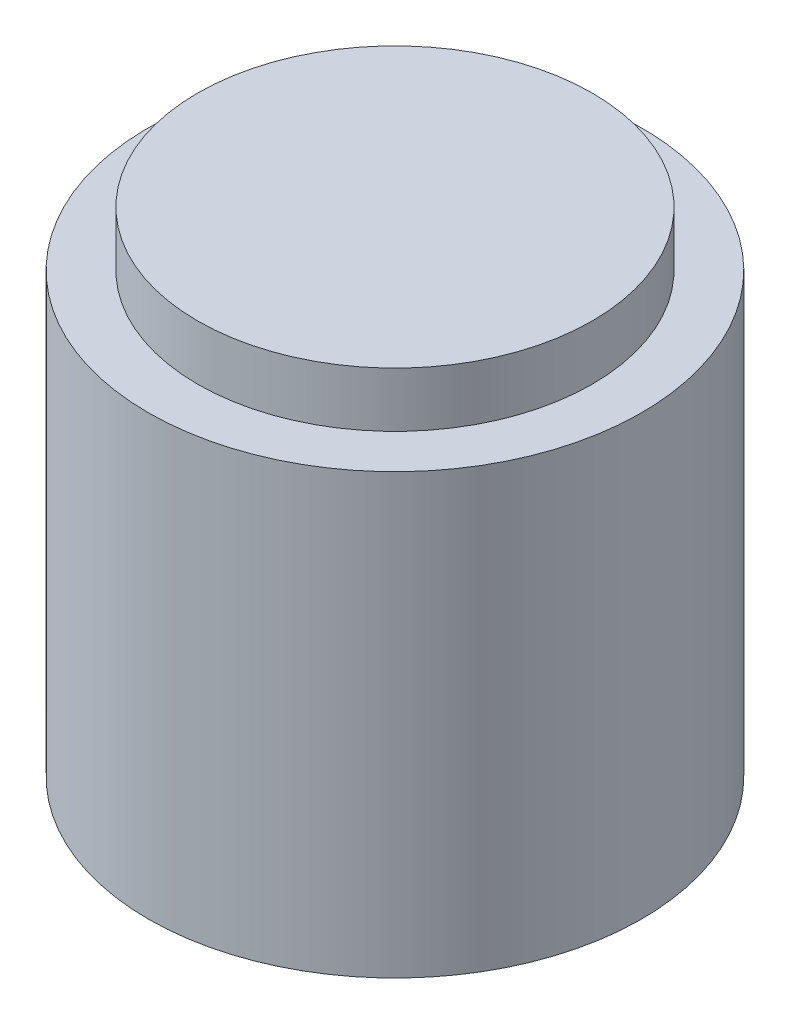
SolidWorks part; units mm, degrees
ref_plane "Front Plane" through (0, 0, 0) normal (0, 0, 1) x (1, 0, 0)
ref_plane "Top Plane" through (0, 0, 0) normal (0, 1, 0) x (1, 0, 0)
ref_plane "Right Plane" through (0, 0, 0) normal (1, 0, 0) x (0, 0, -1)
sketch "Sketch1" plane through (0, 0, 0) normal (0, 1, 0) x (1, 0, 0)
  circle A0 centre (0, 0) radius 7.1438
  dimension "D1" = 14.2875
extrude "Boss-Extrude1" add sketch "Sketch1" along normal blind 12.7
sketch "Sketch2" [suppressed] plane through (0, 12.7, 0) normal (0, 1, 0) x (1, 0, 0)
  line L0 (0, -7.1438) -> (0, -6.35) construction
  line L1 (-7.1438, 0) -> (-6.35, 0) construction
  line L2 (1.27, 6.2217) -> (1.27, 7.03)
  line L4 (-1.27, -7.03) -> (-1.27, -6.2217)
  line L5 (1.0204, 6.2675) -> (1.1479, 7.0509) construction
  line L6 (1.27, -7.03) -> (1.27, -6.2217)
  line L7 (-1.1479, -7.0509) -> (-1.0204, -6.2675) construction
  line L8 (-1.1479, 7.0509) -> (-1.0204, 6.2675) construction
  line L9 (-7.03, 1.27) -> (-6.2217, 1.27)
  line L11 (-7.03, -1.27) -> (-6.2217, -1.27)
  line L13 (-7.0715, 1.0137) -> (-6.2857, 0.9011) construction
  line L14 (-7.0715, -1.0137) -> (-6.2857, -0.9011) construction
  line L15 (0, 6.35) -> (0, 7.1438) construction
  line L17 (-1.27, 6.2217) -> (-1.27, 7.03)
  line L21 (6.2217, -1.27) -> (7.03, -1.27)
  line L22 (6.2217, 1.27) -> (7.03, 1.27)
  line L23 (6.2857, 0.9011) -> (7.0715, 1.0137) construction
  line L24 (6.35, 0) -> (7.1438, 0) construction
  line L25 (6.2857, -0.9011) -> (7.0715, -1.0137) construction
  line L26 (1.0204, -6.2675) -> (1.1479, -7.0509) construction
  arc A0 (1.27, 7.03) -> (-1.27, 7.03) centre (0, 0) ccw
  arc A1 (1.27, 6.2217) -> (-1.27, 6.2217) centre (0, 0) ccw
  arc A2 (-6.2217, 1.27) -> (-6.2217, -1.27) centre (0, 0) ccw
  arc A3 (-7.03, 1.27) -> (-7.03, -1.27) centre (0, 0) ccw
  arc A4 (7.03, -1.27) -> (7.03, 1.27) centre (0, 0) ccw
  arc A5 (6.2217, -1.27) -> (6.2217, 1.27) centre (0, 0) ccw
  arc A6 (-1.27, -7.03) -> (1.27, -7.03) centre (0, 0) ccw
  arc A7 (-1.27, -6.2217) -> (1.27, -6.2217) centre (0, 0) ccw
  circle A8 centre (0, 0) radius 7.1438 construction
  point P7 (0, 0)
  point P9 (0, 0)
  dimension "D1" = 14.2875
  dimension "D2" = 12.7
extrude "Cut-Extrude1" [suppressed] cut sketch "Sketch2" against normal through all
sketch "Sketch3" plane through (0, 12.7, 0) normal (0, 1, 0) x (1, 0, 0)
  circle A0 centre (0, 0) radius 5.715
  dimension "D1" = 11.43
extrude "Boss-Extrude2" add sketch "Sketch3" along normal blind 1.5875
hole_wizard "1/4 (0.25) Diameter Hole1" positions "Sketch6" profile "Sketch7" hole size "1/4" standard "ANSI Inch"
sketch "Sketch6" plane through (0, 0, 0) normal (0, -1, 0) x (-1, 0, 0)
  point P0 (0, 0)
sketch "Sketch7" plane through (0, 0, 0) normal (1, 0, 0) x (0, 0, -1)
  line L0 (0, 0) -> (0, 13.0202)
  line L1 (0, 13.0202) -> (3.175, 11.1125)
  line L2 (3.175, 11.1125) -> (3.175, 0)
  line L5 (3.175, 0) -> (0, 0)
  line L10 (0, 13.0202) -> (-3.175, 11.1125) construction
  line L11 (0, -6.35) -> (0, 107.95) construction
  dimension "Hole Dia." = 6.35
  dimension "Hole Depth" = 11.1125
  dimension "Drill Angle" = 118
